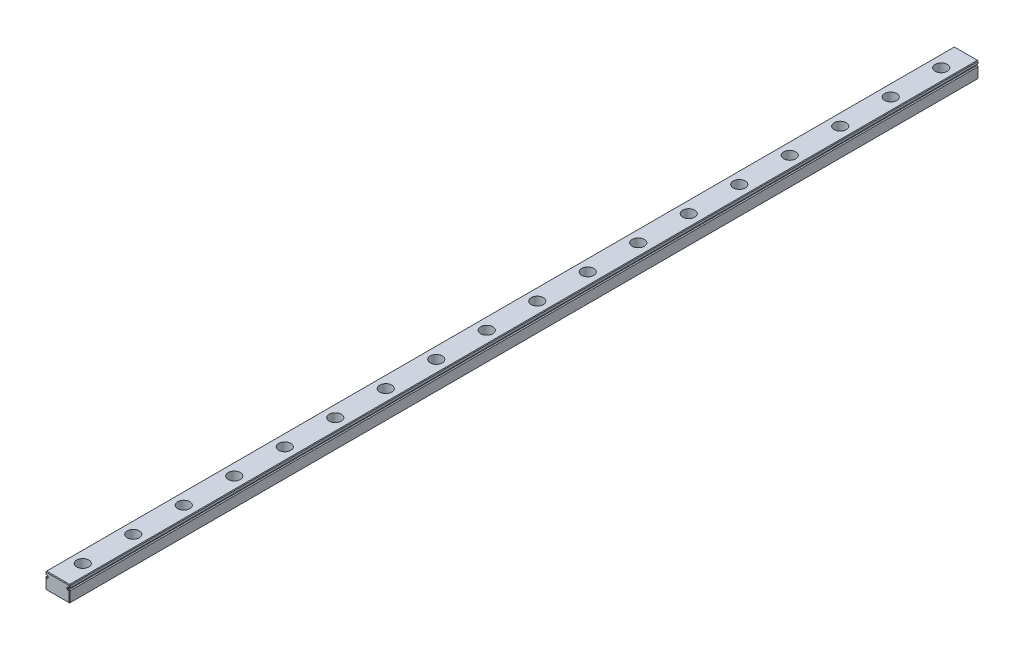
SolidWorks part; units mm, degrees
material "AISI 1045 Steel, cold drawn"
ref_plane "Front Plane" through (0, 0, 0) normal (0, 0, 1) x (1, 0, 0)
ref_plane "Top Plane" through (0, 0, 0) normal (0, 1, 0) x (1, 0, 0)
ref_plane "Right Plane" through (0, 0, 0) normal (1, 0, 0) x (0, 0, -1)
sketch "Sketch1" plane through (0, 0, 0) normal (0, 0, 1) x (1, 0, 0)
  line L0 (0, 0) -> (0, 8) construction
  line L1 (0, 8) -> (12, 8)
  line L2 (0, 0) -> (12, 0)
  line L3 (0, 8) -> (0, 6.75)
  line L4 (0, 6.75) -> (0.5, 6.25) construction
  line L5 (0.5, 6.25) -> (1, 6.25)
  line L6 (0.5, 5.75) -> (0, 5.25) construction
  line L7 (0, 5.25) -> (0, 0)
  line L8 (1, 6.25) -> (1, 5.75)
  line L9 (1, 5.75) -> (0.5, 5.75)
  line L10 (0.5, 5.75) -> (0.75, 6) construction
  line L11 (0.75, 6) -> (0.5, 6.25) construction
  line L12 (0, 6.75) -> (0, 6.559)
  line L13 (0, 5.25) -> (0, 5.441)
  line L14 (6, 8) -> (6, 0) construction
  line L15 (11.25, 6) -> (11.5, 6.25) construction
  line L16 (11.5, 5.75) -> (11.25, 6) construction
  line L17 (11.5, 5.75) -> (12, 5.25) construction
  line L18 (12, 6.75) -> (11.5, 6.25) construction
  line L19 (12, 0) -> (12, 8) construction
  line L20 (12, 5.25) -> (12, 5.441)
  line L21 (12, 6.75) -> (12, 6.559)
  line L22 (11, 5.75) -> (11.5, 5.75)
  line L23 (11, 6.25) -> (11, 5.75)
  line L24 (12, 5.25) -> (12, 0)
  line L25 (11.5, 6.25) -> (11, 6.25)
  line L26 (12, 8) -> (12, 6.75)
  arc A0 (0, 5.441) -> (0.5, 5.75) centre (0, 6) ccw
  arc A1 (0.5, 6.25) -> (0, 6.559) centre (0, 6) ccw
  arc A2 (11.5, 6.25) -> (12, 6.559) centre (12, 6) cw
  arc A3 (12, 5.441) -> (11.5, 5.75) centre (12, 6) cw
  point P4 (1, 6)
  point P28 (11, 6)
  dimension "D1" = 8
  dimension "D2" = 6
  dimension "D3" = 0.5
  dimension "D4" = 45
  dimension "D5" = 2
  dimension "D6" = 1
extrude "Boss-Extrude1" add sketch "Sketch1" along normal blind 450
chamfer "Chamfer1" distance 0.3 angle 45 36 edges at (0, 0, 225) (12, 0, 225) (0, 8, 225) (12, 8, 225) (0.2939, 5.5245, 450) (0.75, 5.75, 450) (1, 6, 450) (0.75, 6.25, 450) (0.2939, 6.4755, 450) (0, 7.2795, 450) (6, 8, 450) (12, 7.2795, 450) (11.7061, 6.4755, 450) (11.25, 6.25, 450) (11, 6, 450) (11.25, 5.75, 450) (11.7061, 5.5245, 450) (12, 2.7205, 450) (6, 0, 450) (0, 2.7205, 450) (12, 2.7205, 0) (11.7061, 5.5245, 0) (11.25, 5.75, 0) (11, 6, 0) (11.25, 6.25, 0) (11.7061, 6.4755, 0) (12, 7.2795, 0) (6, 0, 0) (0, 2.7205, 0) (0.2939, 5.5245, 0) (0.75, 5.75, 0) (1, 6, 0) (0.75, 6.25, 0) (0.2939, 6.4755, 0) (0, 7.2795, 0) (6, 8, 0)
hole_wizard "CBORE for M5 Hex Head Bolt1" positions "3DSketch1" profile "Sketch3" counterbore size "M5" standard "ANSI Metric" end condition through all
sketch3d "3DSketch1"
  line L0 (6, 8, 0) -> (6, 8, 12.5) construction
  line L1 (11.7, 8, 0) -> (0.3, 8, 0) construction
  point P0 (6, 8, 12.5)
  dimension "D1" = 12.5
sketch "Sketch3" plane through (6, 8, 12.5) normal (1, 0, 0) x (0, 0, 1)
  line L0 (0, 0) -> (0, 8)
  line L1 (0, 8) -> (1.75, 8)
  line L3 (1.75, 8) -> (1.75, 4.5)
  line L4 (1.75, 4.5) -> (3, 4.5)
  line L5 (3, 4.5) -> (3, 0)
  line L7 (3, 0) -> (0, 0)
  line L11 (0, -6.35) -> (0, 107.95) construction
  dimension "Thru Hole Dia." = 3.5
  dimension "Thru Hole Depth" = 8
  dimension "C'Bore Dia." = 6
  dimension "C'Bore Depth" = 4.5
pattern_linear "LPattern1" count 18 spacing 25 along (0, 0, 1) of "CBORE for M5 Hex Head Bolt1"
